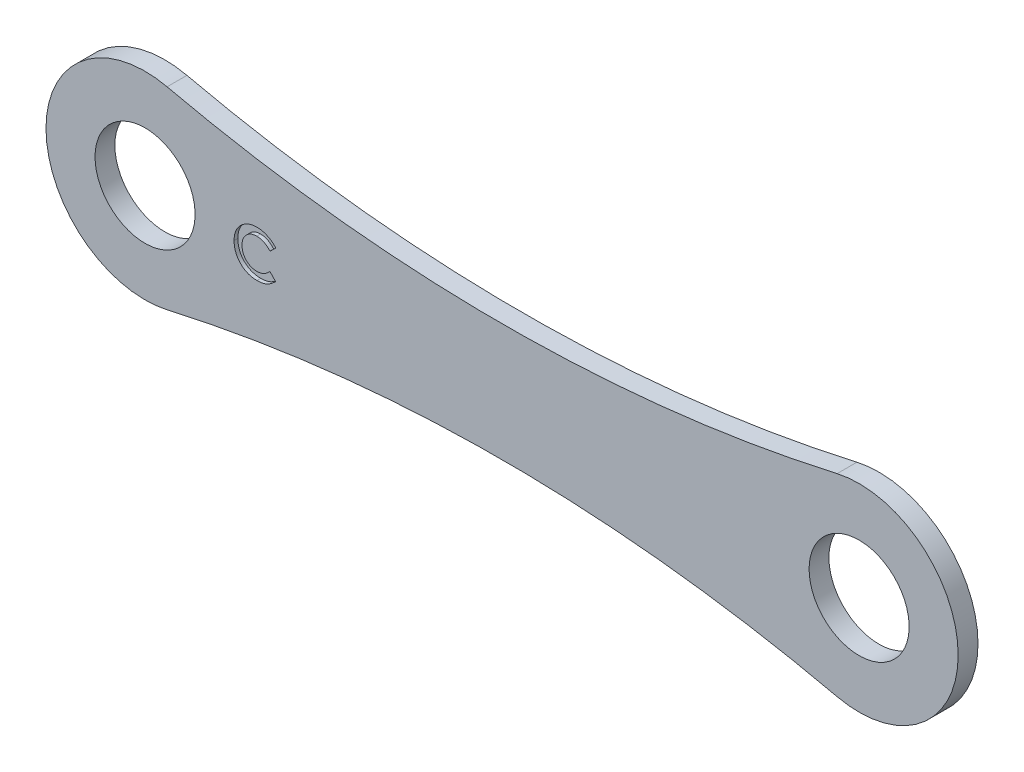
SolidWorks part; units mm, degrees
ref_plane "Plan de face" through (0, 0, 0) normal (1, 0, 0) x (0, 1, 0)
ref_plane "Plan de dessus" through (0, 0, 0) normal (0, 0, 1) x (0, 1, 0)
ref_plane "Plan de droite" through (0, 0, 0) normal (0, 1, 0) x (-1, 0, 0)
sketch "Esquisse1" plane through (0, 0, 0) normal (0, 0, 1) x (0, 1, 0)
  line L0 (0, 0) -> (0, 56.88) construction
  circle A0 centre (0, 0) radius 3.985
  circle A1 centre (0, 56.88) radius 3.985
  circle A2 centre (0, 56.88) radius 7.89
  circle A3 centre (0, 0) radius 7.89
  arc A4 (-7.6924, 1.7546) -> (-7.6924, 55.1254) centre (-124.6877, 28.44) ccw
  arc A5 (7.6924, 1.7546) -> (7.6924, 55.1254) centre (124.6877, 28.44) cw
  dimension "D1" = 56.88
  dimension "D2" = 7.97
  dimension "D3" = 15.78
  dimension "D4" = 120
extrude "Boss.-Extru.1" add sketch "Esquisse1" along normal blind 1.58
sketch "Esquisse2" plane through (0, 0, 1.58) normal (0, 0, 1) x (1, 0, 0)
  text T0 "<b>C</b>"
extrude "Enlèv. mat.-Extru.1" cut sketch "Esquisse2" against normal blind 0.3
